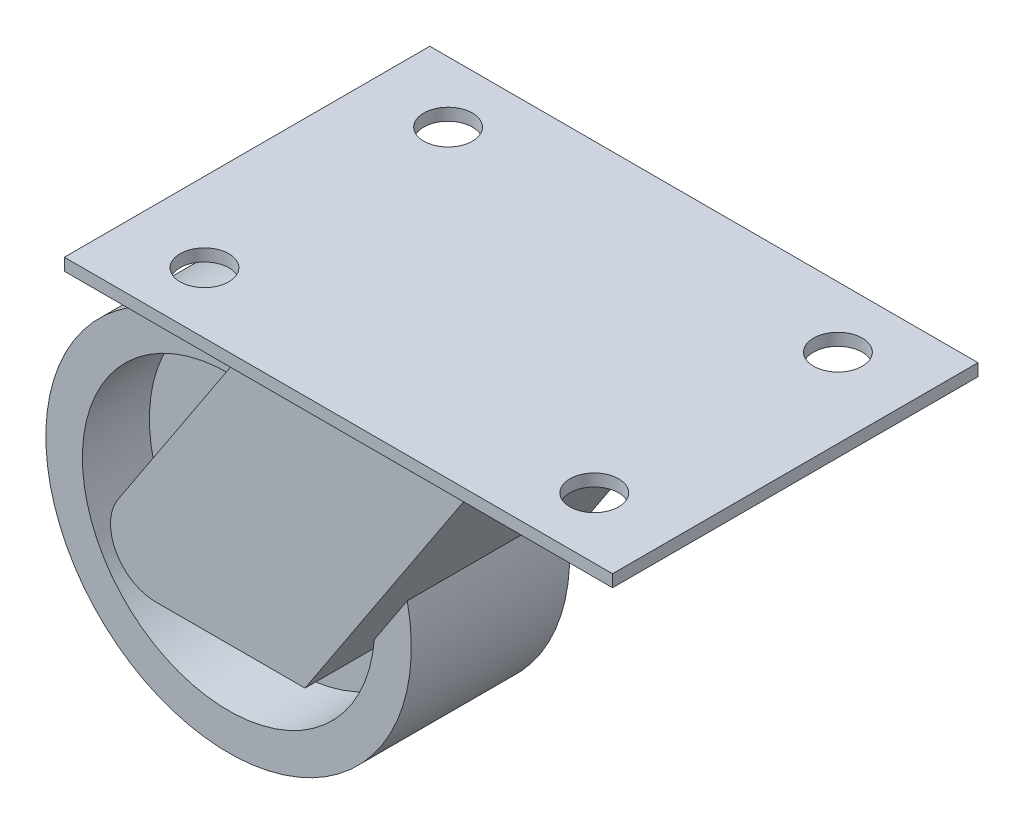
SolidWorks part; units mm, degrees
ref_plane "Alzado" through (0, 0, 0) normal (0, 0, 1) x (1, 0, 0)
ref_plane "Planta" through (0, 0, 0) normal (0, 1, 0) x (1, 0, 0)
ref_plane "Vista lateral" through (0, 0, 0) normal (1, 0, 0) x (0, 0, -1)
sketch "Croquis1" plane through (0, 0, 0) normal (0, 0, 1) x (1, 0, 0)
  circle A0 centre (0, 0) radius 15
  dimension "D1" = 30
extrude "Extruir-Lámina1" add sketch "Croquis1" along normal mid plane 13 thin thin type one direction reverse wall 3
sketch "Croquis2" plane through (0, 0, 0) normal (0, 0, 1) x (1, 0, 0)
  circle A0 centre (0, 0) radius 5
  dimension "D1" = 10
extrude "Saliente-Extruir1" add sketch "Croquis2" along normal mid plane 13 separate body
sketch "Croquis3" plane through (0, 0, 0) normal (0, 0, 1) x (1, 0, 0)
  circle A0 centre (0, 0) radius 12.5
  dimension "D1" = 25
extrude "Saliente-Extruir2" add sketch "Croquis3" along normal mid plane 2 contours A0
sketch "Croquis4" plane through (0, 0, 0) normal (0, 0, 1) x (1, 0, 0)
  circle A0 centre (0, 0) radius 2
  dimension "D1" = 4
extrude "Saliente-Extruir3" add sketch "Croquis4" along normal mid plane 22
sketch "Croquis6" plane through (0, 0, 11) normal (0, 0, 1) x (1, 0, 0)
  line L4 (0, 0) -> (6.873, 0) construction
  line L9 (-4.5819, 2.978) -> (7.9497, 22)
  line L10 (-1.4926, -2.7567) -> (10.7769, -2.7567)
  line L11 (7.9497, 22) -> (27.0863, 22)
  line L12 (10.7769, -2.7567) -> (27.0863, 22)
  arc A1 (-1.4926, -2.7567) -> (-4.5819, 2.978) centre (-1.4926, 0.9428) cw
extrude "Saliente-Extruir4" add sketch "Croquis6" against normal through all
sketch "Croquis7" plane through (0, 22, 0) normal (0, 1, 0) x (1, 0, 0)
  line L0 (7.9497, 11) -> (7.9497, -11) construction
  line L1 (40.0197, -15) -> (-4.9803, -15)
  line L2 (40.0197, -15) -> (40.0197, 15)
  line L3 (40.0197, 15) -> (-4.9803, 15)
  line L4 (-4.9803, -15) -> (-4.9803, 15)
  line L5 (40.0197, -15) -> (-4.9803, 15) construction
  line L6 (40.0197, 15) -> (-4.9803, -15) construction
  line L7 (17.5197, 8.1325) -> (17.5197, 0) construction
  line L8 (17.5197, 0) -> (25.5365, 0) construction
  circle A0 centre (33.5197, 10) radius 2
  circle A1 centre (1.5197, 10) radius 2
  circle A2 centre (33.5197, -10) radius 2
  circle A3 centre (1.5197, -10) radius 2
  point P0 (17.5197, 0)
  point P15 (21.8588, 11)
  dimension "D4" = 4
  dimension "D1" = 9.57
  dimension "D2" = 30
  dimension "D3" = 45
  dimension "D5" = 10
  dimension "D6" = 16
extrude "Saliente-Extruir5" add sketch "Croquis7" against normal blind 1
